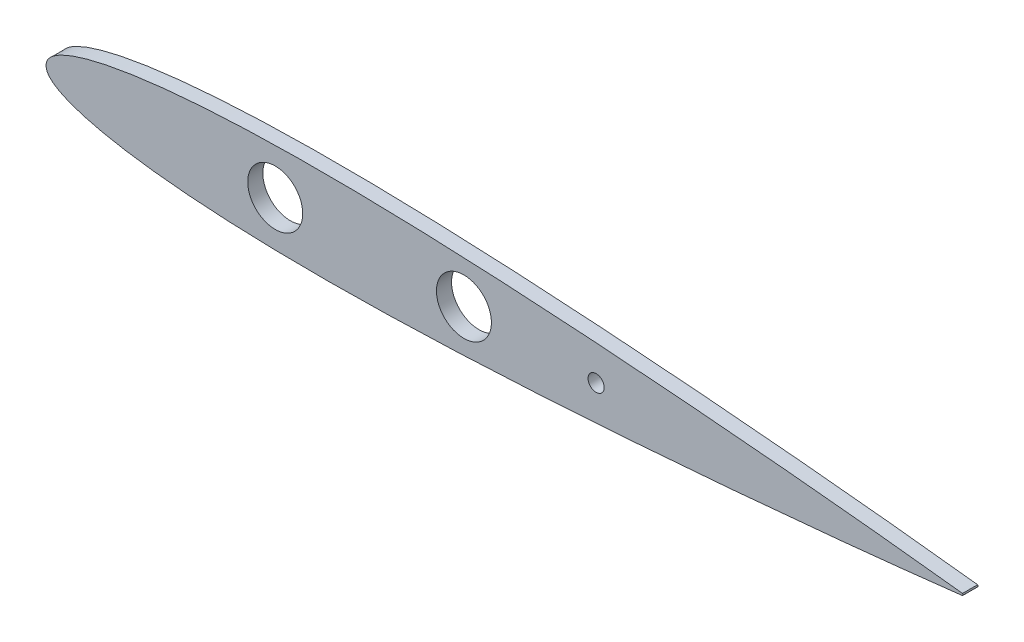
SolidWorks part; units mm, degrees
material "Фанера"
ref_plane "Front Plane" through (0, 0, 0) normal (0, 0, 1) x (1, 0, 0)
ref_plane "Top Plane" through (0, 0, 0) normal (0, 1, 0) x (1, 0, 0)
ref_plane "Right Plane" through (0, 0, 0) normal (1, 0, 0) x (0, 0, -1)
curve "Кривая1"
  spline degree 3 poles (110, 0, 0) (110.0276, -0.2367, 0) (110.0855, -0.7342, 0) (110.5302, -1.4271, 0) (111.1963, -2.0786, 0) (112.1098, -2.7013, 0) (113.2568, -3.2993, 0) (114.6379, -3.8731, 0) (116.2477, -4.4214, 0) (118.0813, -4.9426, 0) (120.1331, -5.4348, 0) (122.3972, -5.8961, 0) (124.8672, -6.3247, 0) (127.537, -6.7187, 0) (130.3997, -7.0764, 0) (133.4488, -7.3965, 0) (136.6771, -7.6776, 0) (140.0777, -7.9187, 0) (143.6433, -8.119, 0) (147.3662, -8.278, 0) (151.2389, -8.3955, 0) (155.2534, -8.4715, 0) (159.4016, -8.5065, 0) (163.6751, -8.501, 0) (168.0653, -8.456, 0) (172.5632, -8.3725, 0) (177.1595, -8.252, 0) (181.8446, -8.096, 0) (186.6087, -7.9062, 0) (191.4413, -7.6846, 0) (196.3316, -7.4331, 0) (201.2684, -7.1538, 0) (206.2396, -6.8489, 0) (211.233, -6.5205, 0) (216.2352, -6.1709, 0) (221.2323, -5.8022, 0) (226.2093, -5.417, 0) (231.1504, -5.0174, 0) (236.0382, -4.6058, 0) (240.8542, -4.1849, 0) (245.5777, -3.7574, 0) (250.1862, -3.3262, 0) (254.6542, -2.8948, 0) (258.9526, -2.4672, 0) (263.0477, -2.0479, 0) (266.899, -1.6426, 0) (270.4558, -1.2586, 0) (273.6512, -0.9053, 0) (276.3854, -0.5964, 0) (278.4526, -0.359, 0) (279.592, -0.2261, 0) (280, -0.1785, 0) knots 0 0 0 0 0.004099 0.008615 0.013935 0.020278 0.027753 0.03641 0.046266 0.05732 0.069559 0.082963 0.097507 0.113164 0.129903 0.14769 0.166492 0.186272 0.206992 0.228612 0.251092 0.274389 0.298458 0.323254 0.348728 0.37483 0.401509 0.42871 0.456376 0.484448 0.512864 0.541558 0.570462 0.599504 0.628607 0.65769 0.686667 0.715445 0.743924 0.771995 0.79954 0.826428 0.852512 0.877624 0.901571 0.924121 0.944989 0.963804 0.980044 0.992855 1 1 1 1
curve "Кривая2"
  spline degree 3 poles (280, 0.1785, 0) (279.592, 0.2261, 0) (278.4526, 0.359, 0) (276.3854, 0.5964, 0) (273.6512, 0.9053, 0) (270.4558, 1.2586, 0) (266.899, 1.6426, 0) (263.0477, 2.0479, 0) (258.9526, 2.4672, 0) (254.6542, 2.8948, 0) (250.1862, 3.3262, 0) (245.5777, 3.7574, 0) (240.8542, 4.1849, 0) (236.0382, 4.6058, 0) (231.1504, 5.0174, 0) (226.2093, 5.417, 0) (221.2323, 5.8022, 0) (216.2352, 6.1709, 0) (211.233, 6.5205, 0) (206.2396, 6.8489, 0) (201.2684, 7.1538, 0) (196.3316, 7.4331, 0) (191.4413, 7.6846, 0) (186.6087, 7.9062, 0) (181.8446, 8.096, 0) (177.1595, 8.252, 0) (172.5632, 8.3725, 0) (168.0653, 8.456, 0) (163.6751, 8.501, 0) (159.4016, 8.5065, 0) (155.2534, 8.4715, 0) (151.2389, 8.3955, 0) (147.3662, 8.278, 0) (143.6433, 8.119, 0) (140.0777, 7.9187, 0) (136.6771, 7.6776, 0) (133.4488, 7.3965, 0) (130.3997, 7.0764, 0) (127.537, 6.7187, 0) (124.8672, 6.3247, 0) (122.3972, 5.8961, 0) (120.1331, 5.4348, 0) (118.0813, 4.9426, 0) (116.2477, 4.4214, 0) (114.6379, 3.8731, 0) (113.2568, 3.2993, 0) (112.1098, 2.7013, 0) (111.1963, 2.0786, 0) (110.5302, 1.4271, 0) (110.0855, 0.7342, 0) (110.0276, 0.2367, 0) (110, 0, 0) knots 0 0 0 0 0.007145 0.019956 0.036196 0.055011 0.075879 0.098429 0.122376 0.147488 0.173572 0.20046 0.228005 0.256076 0.284555 0.313333 0.34231 0.371393 0.400496 0.429538 0.458442 0.487136 0.515552 0.543624 0.57129 0.598491 0.62517 0.651272 0.676746 0.701542 0.725611 0.748908 0.771388 0.793008 0.813728 0.833508 0.85231 0.870097 0.886836 0.902493 0.917037 0.930441 0.94268 0.953734 0.96359 0.972247 0.979722 0.986065 0.991385 0.995901 1 1 1 1
sketch "Эскиз1" plane through (0, 0, 0) normal (0, 0, 1) x (1, 0, 0)
  line L0 (107.6209, 0) -> (300.7166, 0) construction
  line L1 (152.5185, 20.7791) -> (152.5185, -27.7243) construction
  line L2 (110, 19.5459) -> (110, -25.0114) construction
  line L3 (280.0739, 0) -> (280.0739, 37.5235) construction
  line L4 (212.0444, 32.5688) -> (212.0444, -25.0114) construction
  line L5 (187.5185, 30.4265) -> (187.5185, -38.0779) construction
  line L6 (205.5826, 6.8868) -> (205.5826, -6.8868)
  arc A0 (280, 0.1785) -> (280, -0.1785) centre (279.8215, 0) cw
  circle A1 centre (152.5185, 0) radius 5.1
  circle A2 centre (187.5185, 0) radius 5.1
  arc A3 (212.0444, 6.4617) -> (212.0444, -6.4617) centre (212.0444, 0) ccw
  circle A4 centre (212.0444, 0) radius 1.5
  spline S0 degree 3 poles (-1802.3351, -584.8827) (164.5267, 33.7772) (105.6543, 6.1699) (110.5302, -1.4271) (111.1963, -2.0786) (112.1098, -2.7013) (113.2568, -3.2993) (114.6379, -3.8731) (116.2477, -4.4214) (118.0813, -4.9426) (120.1331, -5.4348) (122.3972, -5.8961) (124.8672, -6.3247) (127.537, -6.7187) (130.3997, -7.0764) (133.4488, -7.3965) (136.6771, -7.6776) (140.0777, -7.9187) (143.6433, -8.119) (147.3662, -8.278) (151.2389, -8.3955) (155.2534, -8.4715) (159.4016, -8.5065) (163.6751, -8.501) (168.0653, -8.456) (172.5632, -8.3725) (177.1595, -8.252) (181.8446, -8.096) (186.6087, -7.9062) (191.4413, -7.6846) (196.3316, -7.4331) (201.2684, -7.1538) (206.2396, -6.8489) (211.233, -6.5205) (216.2352, -6.1709) (221.2323, -5.8022) (226.2093, -5.417) (231.1504, -5.0174) (236.0382, -4.6058) (240.8542, -4.1849) (247.0711, -3.6222) (253.1161, -3.0479) (258.9526, -2.4672) (263.0477, -2.0479) (266.899, -1.6426) (270.4558, -1.2586) (273.6512, -0.9053) (276.3854, -0.5964) (359.5279, 8.955) (440.5611, 28.5776) (751.5392, -1938.3855) knots -0.13886 -0.13886 -0.13886 -0.13886 0.004099 0.008615 0.013935 0.020278 0.027753 0.03641 0.046266 0.05732 0.069559 0.082963 0.097507 0.113164 0.129903 0.14769 0.166492 0.186272 0.206992 0.228612 0.251092 0.274389 0.298458 0.323254 0.348728 0.37483 0.401509 0.42871 0.456376 0.484448 0.512864 0.541558 0.570462 0.599504 0.628607 0.65769 0.686667 0.715445 0.743924 0.771995 0.79954 0.852512 0.877624 0.901571 0.924121 0.944989 0.963804 0.980044 0.992855 2.419626 2.419626 2.419626 2.419626 only from (110, 0) to (280, -0.1785) construction
  spline S1 degree 3 poles (751.5383, 1938.3796) (440.561, -28.5775) (359.5279, -8.955) (276.3854, 0.5964) (273.6512, 0.9053) (270.4558, 1.2586) (266.899, 1.6426) (263.0477, 2.0479) (258.9526, 2.4672) (253.1161, 3.0479) (247.0711, 3.6222) (240.8542, 4.1849) (236.0382, 4.6058) (231.1504, 5.0174) (226.2093, 5.417) (221.2323, 5.8022) (216.2352, 6.1709) (211.233, 6.5205) (206.2396, 6.8489) (201.2684, 7.1538) (196.3316, 7.4331) (191.4413, 7.6846) (186.6087, 7.9062) (181.8446, 8.096) (177.1595, 8.252) (172.5632, 8.3725) (168.0653, 8.456) (163.6751, 8.501) (159.4016, 8.5065) (155.2534, 8.4715) (151.2389, 8.3955) (147.3662, 8.278) (143.6433, 8.119) (140.0777, 7.9187) (136.6771, 7.6776) (133.4488, 7.3965) (130.3997, 7.0764) (127.537, 6.7187) (124.8672, 6.3247) (122.3972, 5.8961) (120.1331, 5.4348) (118.0813, 4.9426) (116.2477, 4.4214) (114.6379, 3.8731) (113.2568, 3.2993) (112.1098, 2.7013) (111.1963, 2.0786) (110.5302, 1.4271) (105.6546, -6.1694) (164.5198, -33.7739) (-1801.974, 584.7691) knots -1.419625 -1.419625 -1.419625 -1.419625 0.007145 0.019956 0.036196 0.055011 0.075879 0.098429 0.122376 0.147488 0.20046 0.228005 0.256076 0.284555 0.313333 0.34231 0.371393 0.400496 0.429538 0.458442 0.487136 0.515552 0.543624 0.57129 0.598491 0.62517 0.651272 0.676746 0.701542 0.725611 0.748908 0.771388 0.793008 0.813728 0.833508 0.85231 0.870097 0.886836 0.902493 0.917037 0.930441 0.94268 0.953734 0.96359 0.972247 0.979722 0.986065 0.991385 0.995901 1.138851 1.138851 1.138851 1.138851 only from (280, 0.1785) to (110, 0) construction
  spline S2 degree 3 poles (110, 0) (110.0276, -0.2367) (110.0855, -0.7342) (110.5302, -1.4271) (111.1963, -2.0786) (112.1098, -2.7013) (113.2568, -3.2993) (114.6379, -3.8731) (116.2477, -4.4214) (118.0813, -4.9426) (120.1331, -5.4348) (122.3972, -5.8961) (124.8672, -6.3247) (127.537, -6.7187) (130.3997, -7.0764) (133.4488, -7.3965) (136.6771, -7.6776) (140.0777, -7.9187) (143.6433, -8.119) (147.3662, -8.278) (151.2389, -8.3955) (155.2534, -8.4715) (159.4016, -8.5065) (163.6751, -8.501) (168.0653, -8.456) (172.5632, -8.3725) (177.1595, -8.252) (181.8446, -8.096) (186.6087, -7.9062) (191.4413, -7.6846) (196.3316, -7.4331) (201.2684, -7.1538) (206.2396, -6.8489) (211.233, -6.5205) (216.2352, -6.1709) (221.2323, -5.8022) (226.2093, -5.417) (231.1504, -5.0174) (236.0382, -4.6058) (240.8542, -4.1849) (247.0711, -3.6222) (253.1161, -3.0479) (258.9526, -2.4672) (263.0477, -2.0479) (266.899, -1.6426) (270.4558, -1.2586) (273.6512, -0.9053) (276.3854, -0.5964) (278.4526, -0.359) (279.592, -0.2261) (280, -0.1785) knots 0 0 0 0 0.004099 0.008615 0.013935 0.020278 0.027753 0.03641 0.046266 0.05732 0.069559 0.082963 0.097507 0.113164 0.129903 0.14769 0.166492 0.186272 0.206992 0.228612 0.251092 0.274389 0.298458 0.323254 0.348728 0.37483 0.401509 0.42871 0.456376 0.484448 0.512864 0.541558 0.570462 0.599504 0.628607 0.65769 0.686667 0.715445 0.743924 0.771995 0.79954 0.852512 0.877624 0.901571 0.924121 0.944989 0.963804 0.980044 0.992855 1 1 1 1
  spline S3 degree 3 poles (280, 0.1785) (279.592, 0.2261) (278.4526, 0.359) (276.3854, 0.5964) (273.6512, 0.9053) (270.4558, 1.2586) (266.899, 1.6426) (263.0477, 2.0479) (258.9526, 2.4672) (253.1161, 3.0479) (247.0711, 3.6222) (240.8542, 4.1849) (236.0382, 4.6058) (231.1504, 5.0174) (226.2093, 5.417) (221.2323, 5.8022) (216.2352, 6.1709) (211.233, 6.5205) (206.2396, 6.8489) (201.2684, 7.1538) (196.3316, 7.4331) (191.4413, 7.6846) (186.6087, 7.9062) (181.8446, 8.096) (177.1595, 8.252) (172.5632, 8.3725) (168.0653, 8.456) (163.6751, 8.501) (159.4016, 8.5065) (155.2534, 8.4715) (151.2389, 8.3955) (147.3662, 8.278) (143.6433, 8.119) (140.0777, 7.9187) (136.6771, 7.6776) (133.4488, 7.3965) (130.3997, 7.0764) (127.537, 6.7187) (124.8672, 6.3247) (122.3972, 5.8961) (120.1331, 5.4348) (118.0813, 4.9426) (116.2477, 4.4214) (114.6379, 3.8731) (113.2568, 3.2993) (112.1098, 2.7013) (111.1963, 2.0786) (110.5302, 1.4271) (110.0855, 0.7342) (110.0276, 0.2367) (110, 0) knots 0 0 0 0 0.007145 0.019956 0.036196 0.055011 0.075879 0.098429 0.122376 0.147488 0.20046 0.228005 0.256076 0.284555 0.313333 0.34231 0.371393 0.400496 0.429538 0.458442 0.487136 0.515552 0.543624 0.57129 0.598491 0.62517 0.651272 0.676746 0.701542 0.725611 0.748908 0.771388 0.793008 0.813728 0.833508 0.85231 0.870097 0.886836 0.902493 0.917037 0.930441 0.94268 0.953734 0.96359 0.972247 0.979722 0.986065 0.991385 0.995901 1 1 1 1
  point P23 (212.0444, 6.4617)
  point P24 (212.0444, -6.4617)
  dimension "D1" = 0.2524
  dimension "D5" = 10.2
  dimension "D6" = 6.4617
  dimension "D7" = 3
  dimension "D2" = 170.0739
  dimension "D3" = 42.5185
  dimension "D4" = 68.0296
  dimension "35" = 35
extrude "Бобышка-Вытянуть1" add sketch "Эскиз1" along normal mid plane 2.8 contours L6 S3 S2 A1 A2 | A0 S3 A3 S2 A4 | A3 S3 L6 | L6 S2 A3
equation "\"D3@Эскиз1\"=\"D2@Эскиз1\"/4"
equation "\"D4@Эскиз1\"=\"D2@Эскиз1\"*0.4"
